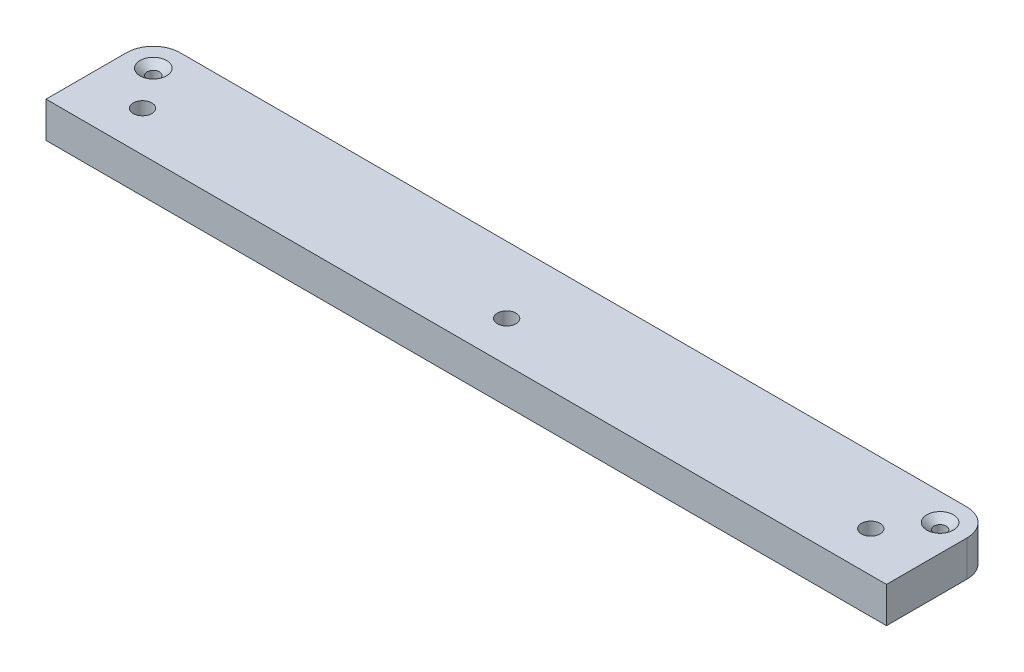
SolidWorks part; units mm, degrees
ref_plane "Front Plane" through (0, 0, 0) normal (0, 0, 1) x (1, 0, 0)
ref_plane "Top Plane" through (0, 0, 0) normal (0, 1, 0) x (1, 0, 0)
ref_plane "Right Plane" through (0, 0, 0) normal (1, 0, 0) x (0, 0, -1)
sketch "Sketch1" plane through (0, 0, 0) normal (0, 1, 0) x (1, 0, 0)
  line L1 (0, 0) -> (298.45, 0)
  line L2 (0, 0) -> (0, 38.1)
  line L3 (0, 38.1) -> (298.45, 38.1)
  line L4 (298.45, 0) -> (298.45, 38.1)
  dimension "D1" = 38.1
  dimension "D2" = 298.45
extrude "Boss-Extrude1" add sketch "Sketch1" along normal blind 12.7
fillet "Fillet1" radius 9.525 2 edges at (298.45, 6.35, -38.1) (0, 6.35, -38.1)
sketch "Sketch2" plane through (0, 12.7, 0) normal (0, 1, 0) x (1, 0, 0)
  line L0 (0, 14.351) -> (298.45, 14.351) construction
  line L1 (0, 28.575) -> (0, 0) construction
  line L2 (298.45, 0) -> (298.45, 28.575) construction
  line L3 (288.925, 38.1) -> (9.525, 38.1) construction
  circle A0 centre (19.939, 14.351) radius 3.302
  circle A1 centre (149.225, 14.351) radius 3.302
  circle A2 centre (278.511, 14.351) radius 3.302
  dimension "D2" = 6.604
  dimension "D1" = 23.749
  dimension "D3" = 19.939
  dimension "D4" = 19.939
extrude "Cut-Extrude1" cut sketch "Sketch2" against normal blind 7.9375
sketch "Sketch4" plane through (0, 0, 0) normal (0, -1, 0) x (1, 0, 0)
  circle A0 centre (19.939, -14.351) radius 1.4224
  circle A1 centre (149.225, -14.351) radius 1.4224
  circle A2 centre (278.511, -14.351) radius 1.4224
  dimension "D1" = 2.8448
extrude "Cut-Extrude2" cut sketch "Sketch4" against normal through all
sketch "Sketch5" plane through (0, 0, 0) normal (0, -1, 0) x (1, 0, 0)
  circle A0 centre (19.939, -14.351) radius 2.413
  circle A1 centre (149.225, -14.351) radius 2.413
  circle A2 centre (278.511, -14.351) radius 2.413
  dimension "D1" = 4.826
extrude "Cut-Extrude3" cut sketch "Sketch5" against normal blind 2.921
sketch "Sketch6" plane through (0, 12.7, 0) normal (0, 1, 0) x (1, 0, 0)
  line L0 (298.45, 28.575) -> (0, 28.575) construction
  line L1 (0, 28.575) -> (0, 0) construction
  line L2 (298.45, 0) -> (298.45, 28.575) construction
  circle A0 centre (9.525, 28.575) radius 2.1844
  circle A1 centre (288.925, 28.575) radius 2.1844
  dimension "D3" = 4.3688
  dimension "D1" = 9.525
  dimension "D2" = 9.525
extrude "Cut-Extrude4" cut sketch "Sketch6" against normal through all contours L0 A1 | A1 L0 | A0
chamfer "Chamfer1" distance 2.54 angle 41 2 edges at (288.925, 12.7, -26.3906) (9.525, 12.7, -26.3906)
sketch "Sketch7" plane through (0, 12.7, 0) normal (0, 1, 0) x (1, 0, 0)
  line L0 (288.925, 38.1) -> (9.525, 38.1) construction
  circle A0 centre (149.225, 28.575) radius 7.239
  dimension "D2" = 14.478
  dimension "D1" = 9.525
extrude "Cut-Extrude5" cut sketch "Sketch7" against normal through all from offset 5.08
